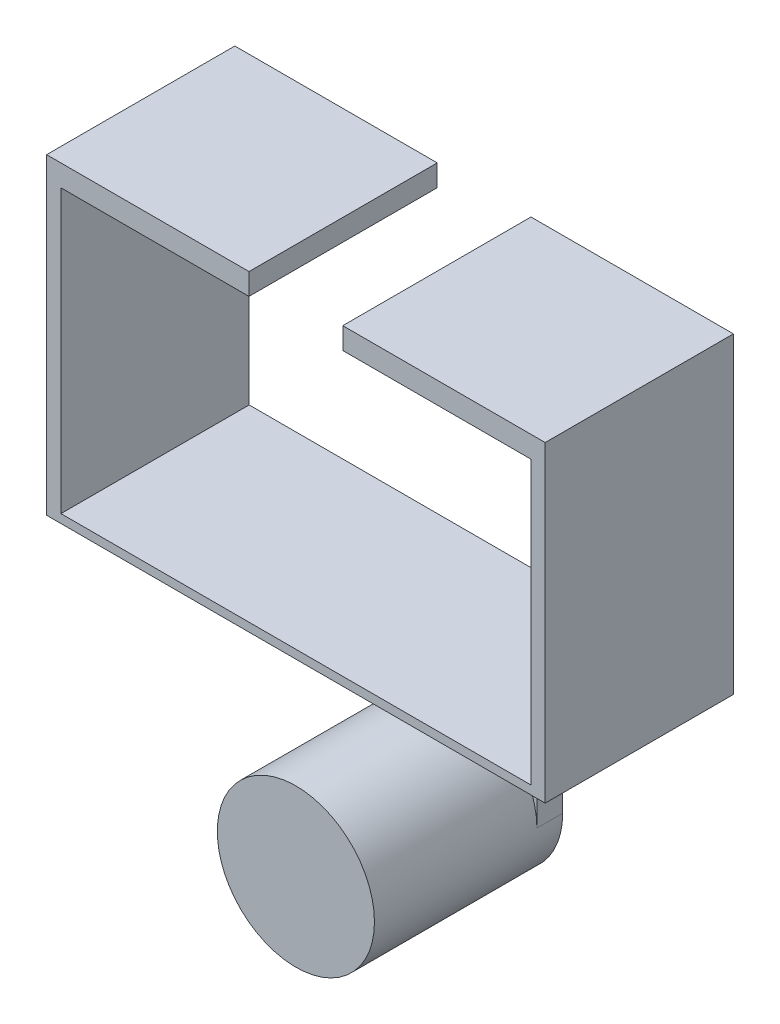
SolidWorks part; units mm, degrees
ref_plane "Front Plane" through (0, 0, 0) normal (0, 0, 1) x (1, 0, 0)
ref_plane "Top Plane" through (0, 0, 0) normal (0, 1, 0) x (1, 0, 0)
ref_plane "Right Plane" through (0, 0, 0) normal (1, 0, 0) x (0, 0, -1)
sketch "Sketch1" plane through (0, 0, 0) normal (0, 0, 1) x (1, 0, 0)
  line L0 (-33.6408, 67.5426) -> (-33.6408, 25.4)
  line L1 (-33.6408, 25.4) -> (33.6408, 25.4)
  line L2 (33.6408, 25.4) -> (33.6408, 67.5426)
  line L3 (33.6408, 67.5426) -> (6.3246, 67.5426)
  line L4 (6.3246, 67.5426) -> (6.3246, 64.6374)
  line L5 (6.3246, 64.6374) -> (31.7043, 64.6374)
  line L6 (31.7043, 64.6374) -> (31.7043, 26.5628)
  line L7 (31.7043, 26.5628) -> (-31.7043, 26.5628)
  line L8 (-31.7043, 26.5628) -> (-31.7043, 64.6374)
  line L9 (-31.7043, 64.6374) -> (-6.3246, 64.6374)
  line L10 (-6.3246, 64.6374) -> (-6.3246, 67.5426)
  line L11 (-6.3246, 67.5426) -> (-33.6408, 67.5426)
  circle A0 centre (0, 0) radius 10.6037
  point P17 (0, 25.4)
  dimension "D6" = 21.2074
  dimension "D1" = 63.4086
  dimension "D2" = 38.0746
  dimension "D3" = 25.3797
  dimension "D4" = 1.1628
  dimension "D5" = 2.9052
  dimension "D7" = 1.9365
  dimension "D8" = 25.4
extrude "Boss-Extrude1" add sketch "Sketch1" along normal blind 25.4
sketch "Sketch3" plane through (0, 0, 0) normal (0, 0, -1) x (-1, 0, 0)
  line L0 (-10.6037, 0) -> (-10.6037, 25.4)
  line L1 (33.6408, 25.4) -> (-33.6408, 25.4) construction
  line L2 (-10.6037, 25.4) -> (10.6037, 25.4)
  line L3 (10.6037, 25.4) -> (10.6037, 0)
  circle A0 centre (0, 0) radius 10.6037 construction
  arc A1 (10.6037, 0) -> (-10.6037, 0) centre (0, 0) cw
  dimension "D1" = 25.4
extrude "Boss-Extrude3" add sketch "Sketch3" against normal blind 3.4767
equation "\"E\"= 10000000'S"
equation "\"Sy\"= 35000"
equation "\"F\"= 500"
equation "\"SF\"= 4"
equation "\"Weight\"= \"F\" * 2"
equation "\"L\"= 1"
equation "\"da\"= ( ( 32 * \"Weight\" * \"L\" * \"SF\" ) / ( 2 * pi * \"Sy\" ) ) ^ ( 1 / 3 )"
equation "\"wb\"= \"da\""
equation "\"tb\"= ( ( \"Weight\" * \"SF\" ) / \"Sy\" ) / \"wb\""
equation "\"wc\"= 2.4964"
equation "\"hc\"= ( ( \"Weight\" * \"SF\" ) / ( \"Sy\" ) ) / ( \"wc\" )"
equation "\"hd\" = 1.499"
equation "\"wd\" = ( ( \"Weight\" * \"SF\" ) / ( \"Sy\" ) ) / \"hd\""
equation "\"we\" = 0.9992"
equation "\"he\"= ( ( \"Weight\" * \"SF\" ) / ( \"Sy\" ) ) / ( \"we\" )"
equation "\"D1@Sketch1\"=\"wc\""
equation "\"d\"= 0"
equation "\"D3@Sketch1\"=\"we\""
equation "\"D5@Sketch1\"=\"he\""
equation "\"D2@Sketch1\"=\"hd\""
equation "\"D4@Sketch1\"=\"hc\""
equation "\"D7@Sketch1\"=\"wd\""
equation "\"D1@Boss-Extrude3\"=\"tb\""
equation "\"D6@Sketch1\"=\"da\""
